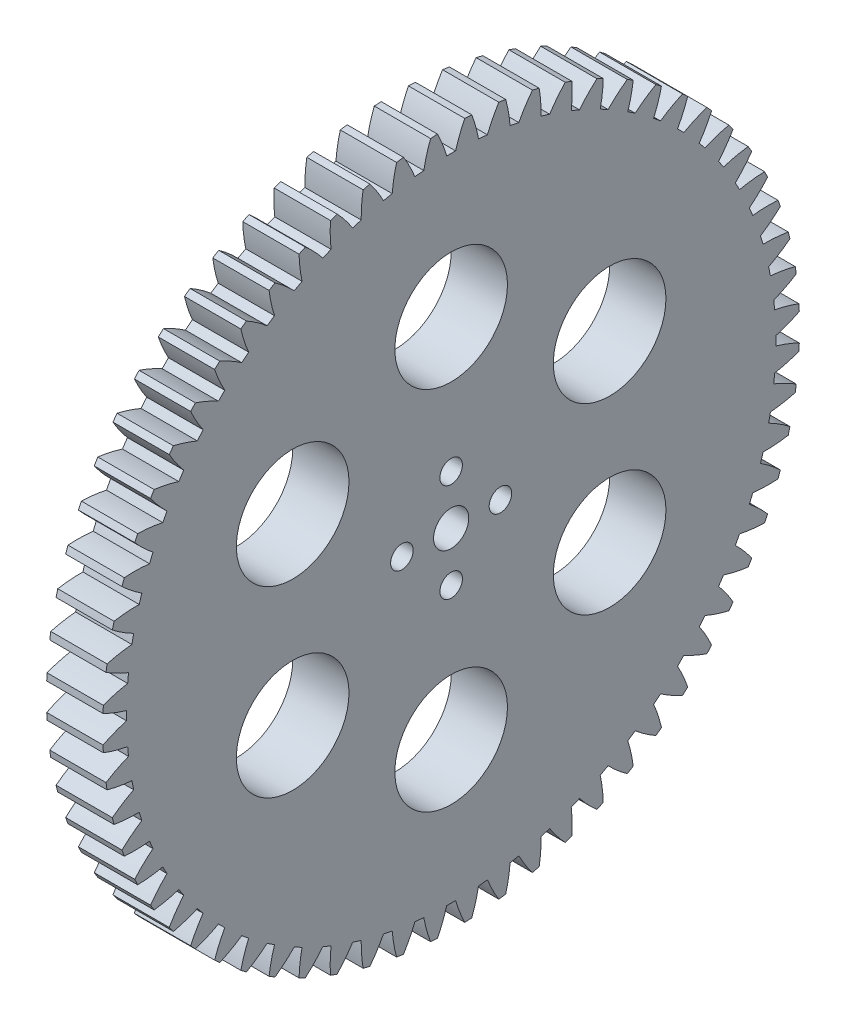
SolidWorks part; units mm, degrees
ref_plane "Plane1" through (0, 0, 0) normal (0, 0, 1) x (1, 0, 0)
ref_plane "Plane2" through (0, 0, 0) normal (0, 1, 0) x (1, 0, 0)
ref_plane "Plane3" through (0, 0, 0) normal (1, 0, 0) x (0, 0, -1)
sketch "HoldingSke" plane through (0, 0, 0) normal (0, 1, 0) x (1, 0, 0)
  line L0 (0, 0) -> (0.2922, -0.5992)
  line L1 (-15, 0) -> (100, 0) construction
  line L2 (0, 0) -> (-2.1039, 2.3779)
  line L3 (0, 0) -> (-11.863, 4.5341)
  line L4 (0, 0) -> (3.7858, 7.762)
  line L5 (0, 0) -> (-46.8476, -17.4728)
  line L6 (0, 0) -> (-6.6317, -4.4744)
  line L7 (-2.1039, 2.3779) -> (8.6586, 51.2059)
  line L8 (-76.2, 54.61) -> (-75.3, 54.61)
  line L9 (-71.009, 38.7566) -> (-53.1078, 45.2721)
  line L10 (-76.2, 71.12) -> (104.1128, 71.12)
  line L11 (0, 0) -> (-8, 0)
  line L12 (-76.2, 101.6) -> (-76.147, 101.6)
  line L13 (24.9733, 27.94) -> (52.9518, 28.4284)
  line L14 (24.9733, 27.94) -> (24.9743, 27.94)
  line L15 (24.9733, 27.94) -> (100.4006, 29.5858)
  line L16 (-63.627, -1.5) -> (-12.827, -1.5)
  circle A0 centre (0, 0) radius 2.5
  circle A1 centre (0, 0) radius 37.5
  circle A2 centre (0, 0) radius 37.5
  circle A3 centre (0, 0) radius 2.5
  dimension "MHD" = 75
  dimension "Hub_dia" = 75
  dimension "Bore" = 5
  dimension "MBD" = 5
  dimension "Num_teeth" = 64
  dimension "Pitch" = 0.6667
  dimension "Overall_len" = 50
  dimension "Show_teeth" = 64
  dimension "Thickness" = 8
  dimension "OAL" = 50.0001
  dimension "T_dim" = 0.9
  dimension "Ap" = 20
  dimension "H" = 19.05
  dimension "Pitch_radius" = 180.3128
  dimension "Width" = 8
  dimension "Backlash" = 0.053
  dimension "Addendum_fac" = 1
  dimension "Dedendum_fac" = 1.25
  dimension "Clearance_fac" = 0.25
  dimension "Dedendum_add" = 0.001
  dimension "Module" = 1.5
sketch "BasProSke" plane through (0, 0, 0) normal (0, 1, 0) x (1, 0, 0)
  line L0 (-10, 0) -> (60, 0) construction
  line L1 (0, 0) -> (0, 49.5)
  line L2 (0, 0) -> (8, 0)
  line L3 (8, 0) -> (8, 49.5)
  line L4 (8, 49.5) -> (0, 49.5)
  dimension "Thickness" = 8
  dimension "Diameter" = 99
revolve "Base-Revolve" add sketch "BasProSke" angle 360 about L0
sketch "TooCutSke" plane through (0, 0, 0) normal (1, 0, 0) x (0, 0, -1)
  line L1 (0, 0) -> (0, 107) construction
  line L2 (0, 0) -> (-1.2707, 47.9832) construction
  line L3 (0, 0) -> (-4.7093, 95.8599) construction
  line L4 (-1.2707, 47.9832) -> (-2.3546, 47.9299) construction
  arc A0 (0.6351, 46.1196) -> (-0.6351, 46.1196) centre (0, 0) ccw
  arc A1 (1.9477, 49.4871) -> (-1.9477, 49.4871) centre (0, 0) ccw
  circle A2 centre (0, 0) radius 48 construction
  circle A3 centre (0, 0) radius 45.1052 construction
  arc A4 (-0.6351, 46.1196) -> (-1.9477, 49.4871) centre (-19.101, 40.8612) ccw
  arc A5 (1.9477, 49.4871) -> (0.6351, 46.1196) centre (19.101, 40.8612) ccw
  dimension "Root_dia" = 92.248
  dimension "Overcut_dia" = 99.0508
  dimension "Pitch_dia" = 96
  dimension "Base_dia" = 90.2105
  dimension "Flank_rad" = 19.2
  dimension "Half_ang" = 2.813
  dimension "Half_CT" = 1.0852
extrude "ToothCut" cut sketch "TooCutSke" along normal through all
fillet "Breaks" [suppressed] radius 0.03
fillet "RootFillets" [suppressed] radius 0.376
pattern_circular "TeethCuts" count 64 every 5.625 about axis through (-10, 0, 0) along (1, 0, 0) of "ToothCut", "RootFillets", "Breaks"
sketch "HubNeaOneSke" plane through (0, 0, 0) normal (-1, 0, 0) x (0, 0, 1)
  circle A0 centre (0, 0) radius 37.5
  dimension "Diameter" = 75
extrude "HubNearOne" [suppressed] add sketch "HubNeaOneSke" along normal blind 42.0001
sketch "HubNeaBotSke" plane through (0, 0, 0) normal (-1, 0, 0) x (0, 0, 1)
  circle A0 centre (0, 0) radius 37.5
  dimension "Diameter" = 75
extrude "HubNearBoth" [suppressed] add sketch "HubNeaBotSke" along normal blind 21
ref_plane "FarPln" through (8, 0, 0) normal (1, 0, 0) x (0, 0, -1)
sketch "HubFarSke" plane through (8, 0, 0) normal (1, 0, 0) x (0, 0, -1)
  circle A0 centre (0, 0) radius 37.5
  dimension "Diameter" = 75
extrude "HubFar" [suppressed] add sketch "HubFarSke" along normal blind 21
sketch "BorSke" plane through (0, 0, 0) normal (1, 0, 0) x (0, 0, -1)
  circle A0 centre (0, 0) radius 2.5
  dimension "Diameter" = 5
extrude "Bore" cut sketch "BorSke" along normal mid plane 100.0001
sketch "KeySke" plane through (0, 0, 0) normal (1, 0, 0) x (0, 0, -1)
  line L0 (-1, 0) -> (-1, 3.4)
  line L1 (-1, 3.4) -> (1, 3.4)
  line L2 (1, 3.4) -> (1, 0)
  line L3 (0, 0) -> (0, 34) construction
  line L4 (-1, 0) -> (1, 0)
  dimension "Offset" = 3.4
  dimension "Width" = 2
extrude "Keyway" [suppressed] cut sketch "KeySke" along normal mid plane 100.0001
pattern_circular "Keyway2" [suppressed] count 2 every 90 about axis through (-10, 0, 0) along (1, 0, 0)
sketch "草图1" plane through (0, 0, 0) normal (1, 0, 0) x (0, 0, -1)
  circle A0 centre (0, 0) radius 7 construction
  circle A1 centre (0, 7) radius 1.6
  circle A2 centre (7, 0) radius 1.6
  circle A3 centre (0, -7) radius 1.6
  circle A4 centre (-7, 0) radius 1.6
  circle A5 centre (0, 0) radius 26 construction
  circle A6 centre (0, 26) radius 8
  circle A7 centre (22.5167, 13) radius 8
  circle A8 centre (22.5167, -13) radius 8
  circle A9 centre (0, -26) radius 8
  circle A10 centre (-22.5167, -13) radius 8
  circle A11 centre (-22.5167, 13) radius 8
  point P14 (0, 0)
  point P27 (0, 0)
  dimension "D1" = 14
  dimension "D2" = 3.2
  dimension "D4" = 52
  dimension "D5" = 16
  dimension "D3" = 4
  dimension "D6" = 6
extrude "切除-拉伸2" cut sketch "草图1" along normal through all
equation "' \"Module@HoldingSke\" = 6.35"
equation "' \"Num_teeth@HoldingSke\" = 12"
equation "' \"Ap@HoldingSke\" =  20"
equation "' \"Ap@HoldingSke\" = 20"
equation "' \"Width@HoldingSke\" = 0.5 * 25.4"
equation "' \"Hub_dia@HoldingSke\"= 1 * 25.4"
equation "' \"Hub_dia@HoldingSke\" = 1 * 25.4"
equation "' \"Overall_len@HoldingSke\" = 1.0 * 25.4"
equation "' \"Bore@HoldingSke\" = 0.75 * 25.4"
equation "' \"T_dim@HoldingSke\" = 0.1 * 25.4"
equation "' \"Width@KeySke\" = 0.25 * 25.4"
equation "' \"Show_teeth@HoldingSke\" = 13"
equation "' \"Backlash@HoldingSke\" = 0.009 * 25.4"
equation "' \"Addendum_fac@HoldingSke\" = 1.0"
equation "' \"Dedendum_fac@HoldingSke\" = 1.25"
equation "' \"Dedendum_add@HoldingSke\" = 0.00005 * 25.4"
equation "' \"Clearance_fac@HoldingSke\" = 0.25"
equation "\"Pitch@HoldingSke\" = 1 / \"Module@HoldingSke\""
equation "\"Overcut_dia@TooCutSke\" = (\"Num_teeth@HoldingSke\" + 2 * \"Addendum_fac@HoldingSke\") / \"Pitch@HoldingSke\" + 0.002 * 25.4"
equation "\"Pitch_dia@TooCutSke\" = \"Num_teeth@HoldingSke\" / \"Pitch@HoldingSke\""
equation "\"Base_dia@TooCutSke\" = \"Num_teeth@HoldingSke\" / \"Pitch@HoldingSke\" * cos((\"Ap@HoldingSke\"  * 3.14159265 / 180))"
equation "\"Root_dia@TooCutSke\" = (\"Num_teeth@HoldingSke\" + 2) / \"Pitch@HoldingSke\" - 2 * (\"Addendum_fac@HoldingSke\" + \"Dedendum_fac@HoldingSke\") / \"Pitch@HoldingSke\" - \"Dedendum_add@HoldingSke\" * 2"
equation "\"Half_ang@TooCutSke\" = 180 / \"Num_teeth@HoldingSke\""
equation "\"Half_CT@TooCutSke\" = \"Num_teeth@HoldingSke\" / \"Pitch@HoldingSke\" * sin((3.14159265 / 2 / \"Num_teeth@HoldingSke\")) / 2 - 7 * \"Backlash@HoldingSke\" / 4"
equation "\"Flank_rad@TooCutSke\" = \"Num_teeth@HoldingSke\" / \"Pitch@HoldingSke\" / 5"
equation "\"Radius@RootFillets\" = \"Clearance_fac@HoldingSke\" / \"Pitch@HoldingSke\" + \"Dedendum_add@HoldingSke\""
equation "\"Break_rad@Breaks\" = 0.02 / \"Pitch@HoldingSke\""
equation "\"Thickness@HoldingSke\" = \"Width@HoldingSke\""
equation "\"OAL@HoldingSke\" = \"Thickness@HoldingSke\""
equation "\"MHD@HoldingSke\" = (\"Num_teeth@HoldingSke\" + 2) / \"Pitch@HoldingSke\" - 2 * (\"Addendum_fac@HoldingSke\" + \"Dedendum_fac@HoldingSke\")  / \"Pitch@HoldingSke\" - \"Dedendum_add@HoldingSke\" * 2"
equation "\"MBD@HoldingSke\" = (\"Num_teeth@HoldingSke\" + 2) / \"Pitch@HoldingSke\" - 2 * (\"Addendum_fac@HoldingSke\" + \"Dedendum_fac@HoldingSke\")  / \"Pitch@HoldingSke\" - \"Dedendum_add@HoldingSke\" * 2 - 0.002 * 25.4"
equation "\"MHD@HoldingSke\" = ((sgn( \"MHD@HoldingSke\" - \"Hub_dia@HoldingSke\" )-1)*( \"MHD@HoldingSke\" - \"Hub_dia@HoldingSke\" ))/-2+ \"Hub_dia@HoldingSke\""
equation "\"MBD@HoldingSke\" = ((sgn( \"MBD@HoldingSke\" - \"Bore@HoldingSke\" )-1)*( \"MBD@HoldingSke\" - \"Bore@HoldingSke\" ))/-2+ \"Bore@HoldingSke\""
equation "\"OAL@HoldingSke\" = ((sgn( \"OAL@HoldingSke\" - \"Overall_len@HoldingSke\" )+1)*( \"OAL@HoldingSke\" - \"Overall_len@HoldingSke\" ))/2 + \"Overall_len@HoldingSke\" + 0.000002 * 25.4"
equation "\"Num_teeth@TeethCuts\" = int( \"Show_teeth@HoldingSke\" ) + 1"
equation "\"Num_teeth@TeethCuts\" = ((sgn( \"Num_teeth@TeethCuts\" - \"Num_teeth@HoldingSke\" )-1)*( \"Num_teeth@TeethCuts\" - \"Num_teeth@HoldingSke\" ))/-2+ \"Num_teeth@HoldingSke\""
equation "\"Num_teeth@TeethCuts\" = ((sgn( \"Num_teeth@TeethCuts\" - 2.0)+1)*( \"Num_teeth@TeethCuts\" - 2.0))/2 +2.0"
equation "\"Angle@TeethCuts\" = 360.0 / \"Num_teeth@HoldingSke\""
equation "\"Diameter@BasProSke\" = (\"Num_teeth@HoldingSke\" + 2 * \"Addendum_fac@HoldingSke\") / \"Pitch@HoldingSke\""
equation "\"Thickness@BasProSke\"  = \"Thickness@HoldingSke\""
equation "' \"Fillet_rad@BasProSke\" =  \"Thickness@HoldingSke\" * 0.05"
equation "' \"Fillet_rad@BasProSke\" = \"Thickness@HoldingSke\" * 0.05"
equation "\"MHD@HoldingSke\" = ((sgn( \"MHD@HoldingSke\" - \"Root_dia@TooCutSke\" )-1)*( \"MHD@HoldingSke\" - \"Root_dia@TooCutSke\" ))/-2+ \"Root_dia@TooCutSke\""
equation "\"Diameter@HubNeaOneSke\" = \"MHD@HoldingSke\""
equation "\"Length@HubNearOne\" = \"OAL@HoldingSke\" - \"Thickness@BasProSke\""
equation "\"Diameter@HubNeaBotSke\" = \"MHD@HoldingSke\""
equation "\"Length@HubNearBoth\" = ( \"OAL@HoldingSke\" - \"Thickness@BasProSke\" ) / 2.0"
equation "\"Thickness@FarPln\" = \"Thickness@BasProSke\""
equation "\"Diameter@HubFarSke\" = \"MHD@HoldingSke\""
equation "\"Length@HubFar\" = ( \"OAL@HoldingSke\" - \"Thickness@BasProSke\" ) / 2.0"
equation "\"Diameter@BorSke\" = \"MBD@HoldingSke\""
equation "\"D1@Bore\" = \"OAL@HoldingSke\" * 2.0"
equation "\"D1@Keyway\" = \"OAL@HoldingSke\" * 2.0"
equation "\"Offset@KeySke\" = \"T_dim@HoldingSke\" + \"MBD@HoldingSke\" / 2.0"
